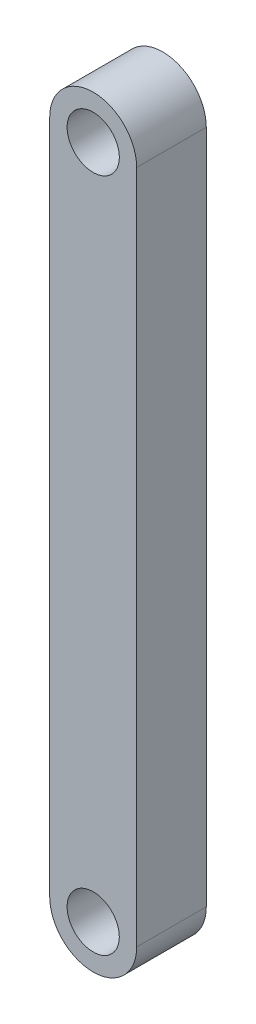
SolidWorks part; units mm, degrees
ref_plane "Front Plane" through (0, 0, 0) normal (0, 0, 1) x (1, 0, 0)
ref_plane "Top Plane" through (0, 0, 0) normal (0, 1, 0) x (1, 0, 0)
ref_plane "Right Plane" through (0, 0, 0) normal (1, 0, 0) x (0, 0, -1)
sketch "Sketch1" plane through (0, 0, 0) normal (0, 0, 1) x (1, 0, 0)
  line L0 (0, 0) -> (0, 38.8) construction
  line L1 (-2.5, 0) -> (-2.5, 38.8)
  line L2 (2.5, 0) -> (2.5, 38.8)
  arc A0 (-2.5, 0) -> (2.5, 0) centre (0, 0) ccw
  arc A1 (2.5, 38.8) -> (-2.5, 38.8) centre (0, 38.8) ccw
  circle A2 centre (0, 0) radius 1.5
  circle A3 centre (0, 38.8) radius 1.5
  point P3 (0, 19.4)
  dimension "D1" = 38.8
  dimension "D2" = 2.5
  dimension "D3" = 3
  dimension "D4" = 1
extrude "Boss-Extrude2" add sketch "Sketch1" along normal blind 4
